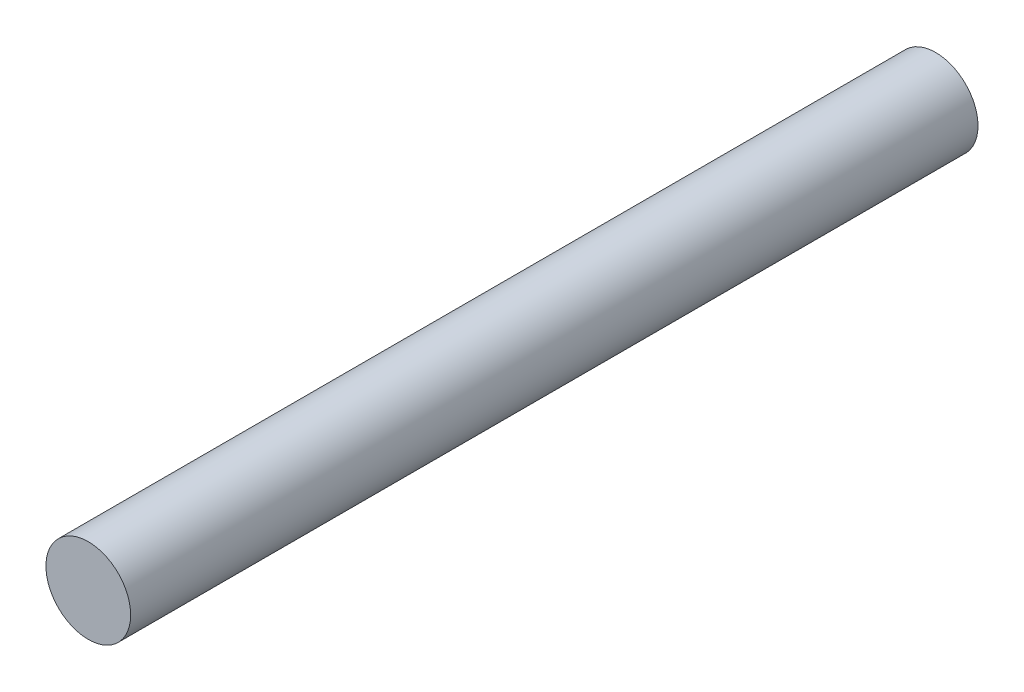
SolidWorks part; units mm, degrees
ref_plane "前视基准面" through (0, 0, 0) normal (0, 0, 1) x (1, 0, 0)
ref_plane "上视基准面" through (0, 0, 0) normal (0, 1, 0) x (1, 0, 0)
ref_plane "右视基准面" through (0, 0, 0) normal (1, 0, 0) x (0, 0, -1)
other "Configuration Table"
sketch "草图1" plane through (0, 0, 0) normal (0, 0, 1) x (1, 0, 0)
  circle A0 centre (0, 0) radius 1.5
extrude "凸台-拉伸1" add sketch "草图1" along normal blind 30
